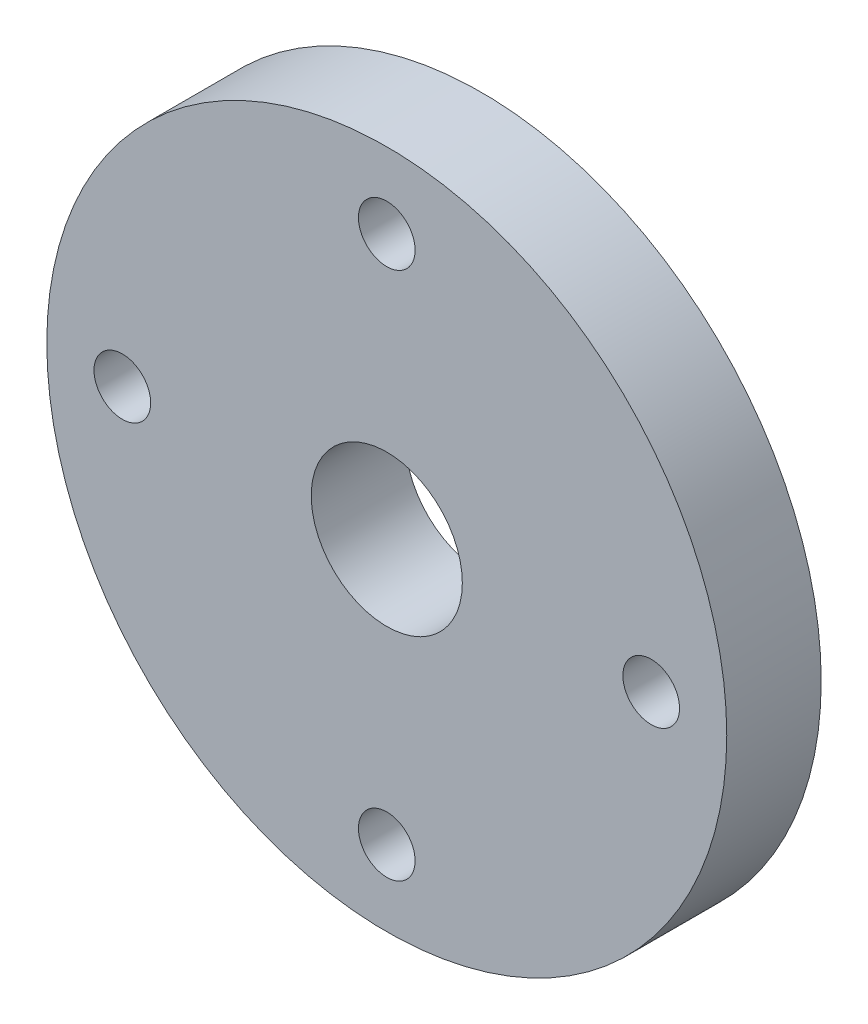
SolidWorks part; units mm, degrees
material "Acrylic (Medium-high impact)"
ref_plane "Front Plane" through (0, 0, 0) normal (0, 0, 1) x (1, 0, 0)
ref_plane "Top Plane" through (0, 0, 0) normal (0, 1, 0) x (1, 0, 0)
ref_plane "Right Plane" through (0, 0, 0) normal (1, 0, 0) x (0, 0, -1)
sketch "Sketch2" plane through (0, 0, 0) normal (0, 0, 1) x (1, 0, 0)
  circle A0 centre (0, 0) radius 18
extrude "Boss-Extrude1" add sketch "Sketch2" along normal blind 5
sketch "Sketch3" plane through (0, 0, 5) normal (0, 0, 1) x (1, 0, 0)
  circle A0 centre (0, 0) radius 4
  dimension "D1" = 0
extrude "Cut-Extrude1" cut sketch "Sketch3" against normal blind 122
sketch "Sketch4" plane through (0, 0, 0) normal (0, 0, -1) x (-1, 0, 0)
  line L0 (0, 35.8542) -> (0, -31.7202) construction
  line L1 (-38.0006, 0) -> (55.6495, 0) construction
  circle A0 centre (0, 0) radius 14 construction
  circle A1 centre (0, 14) radius 1.5
  circle A2 centre (14, 0) radius 1.5
  circle A3 centre (0, -14) radius 1.5
  circle A4 centre (-14, 0) radius 1.5
extrude "Cut-Extrude2" cut sketch "Sketch4" against normal blind 5
